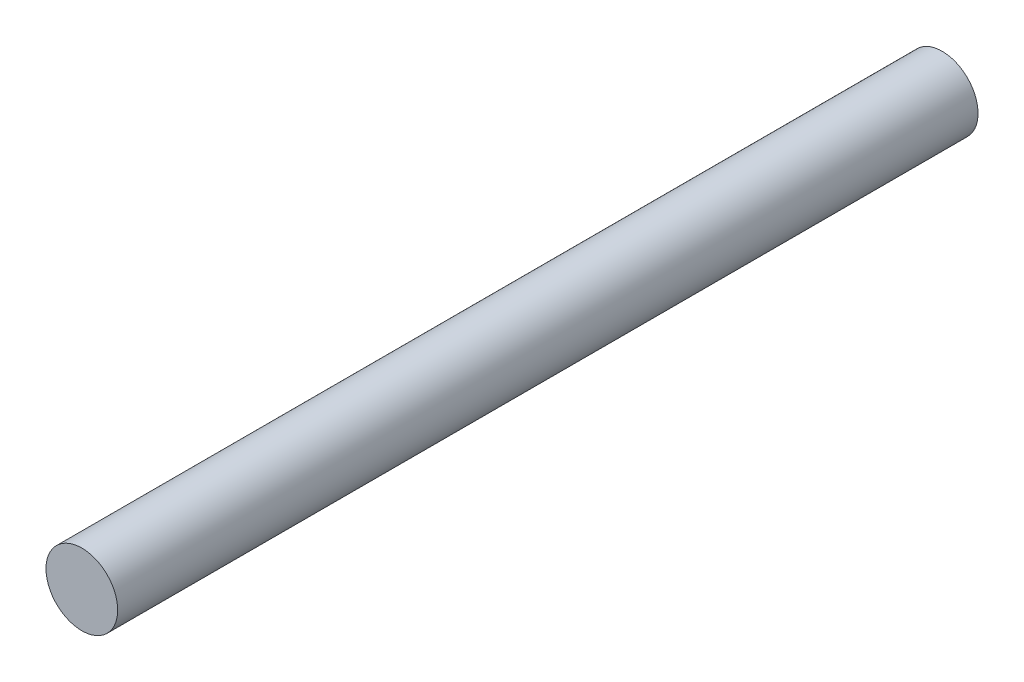
SolidWorks part; units mm, degrees
ref_plane "Plan de face" through (0, 0, 0) normal (0, 0, 1) x (1, 0, 0)
ref_plane "Plan de dessus" through (0, 0, 0) normal (0, 1, 0) x (1, 0, 0)
ref_plane "Plan de droite" through (0, 0, 0) normal (1, 0, 0) x (0, 0, -1)
sketch "Esquisse1" plane through (0, 0, 0) normal (0, 0, 1) x (1, 0, 0)
  circle A0 centre (0, 0) radius 12.7
  dimension "D1" = 25.4
extrude "Boss.-Extru.1" add sketch "Esquisse1" along normal mid plane 304.8
